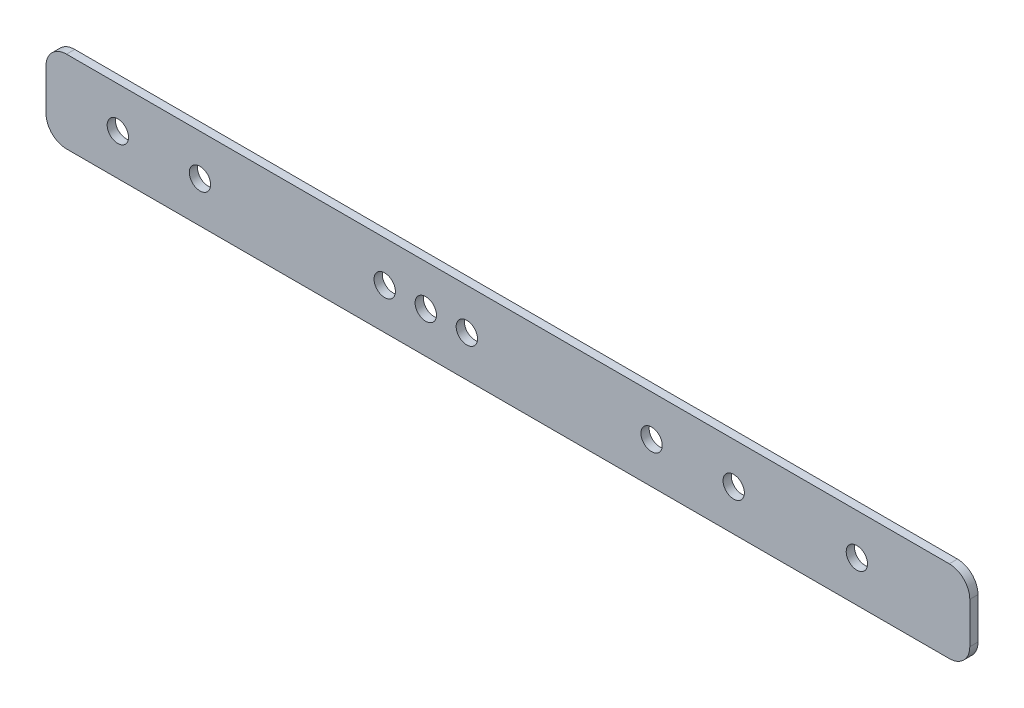
SolidWorks part; units mm, degrees
material "Thornel Mat VMA"
ref_plane "前视基准面" through (0, 0, 0) normal (0, 0, 1) x (1, 0, 0)
ref_plane "上视基准面" through (0, 0, 0) normal (0, 1, 0) x (1, 0, 0)
ref_plane "右视基准面" through (0, 0, 0) normal (1, 0, 0) x (0, 0, -1)
sketch "草图1" plane through (0, 0, 0) normal (0, 0, 1) x (1, 0, 0)
  line L1 (-112.5, 10) -> (112.5, 10)
  line L2 (-112.5, 10) -> (-112.5, -10)
  line L3 (-112.5, -10) -> (112.5, -10)
  line L4 (112.5, 10) -> (112.5, -10)
  line L5 (-112.5, 10) -> (112.5, -10) construction
  line L6 (-112.5, -10) -> (112.5, 10) construction
  point P0 (0, 0)
  dimension "D1" = 225
  dimension "D2" = 20
extrude "凸台-拉伸1" add sketch "草图1" along normal blind 2
sketch "草图2" plane through (0, 0, 0) normal (0, 0, -1) x (-1, 0, 0)
  circle A0 centre (95, 0) radius 2.6 construction
  circle A1 centre (75, 0) radius 2.6 construction
  circle A2 centre (30, 0) radius 2.6 construction
  circle A3 centre (20, 0) radius 2.6 construction
  circle A4 centre (10, 0) radius 2.6 construction
  circle A5 centre (-35, 0) radius 2.6 construction
  circle A6 centre (-55, 0) radius 2.6 construction
  circle A7 centre (-85, 0) radius 2.6 construction
  circle A8 centre (95, 0) radius 2.6
  circle A9 centre (75, 0) radius 2.6
  circle A10 centre (30, 0) radius 2.6
  circle A11 centre (20, 0) radius 2.6
  circle A12 centre (10, 0) radius 2.6
  circle A13 centre (-35, 0) radius 2.6
  circle A14 centre (-55, 0) radius 2.6
  circle A15 centre (-85, 0) radius 2.6
extrude "切除-拉伸1" cut sketch "草图2" against normal through all
fillet "圆角1" radius 5 4 edges at (112.5, -10, 1) (-112.5, 10, 1) (112.5, 10, 1) (-112.5, -10, 1)
